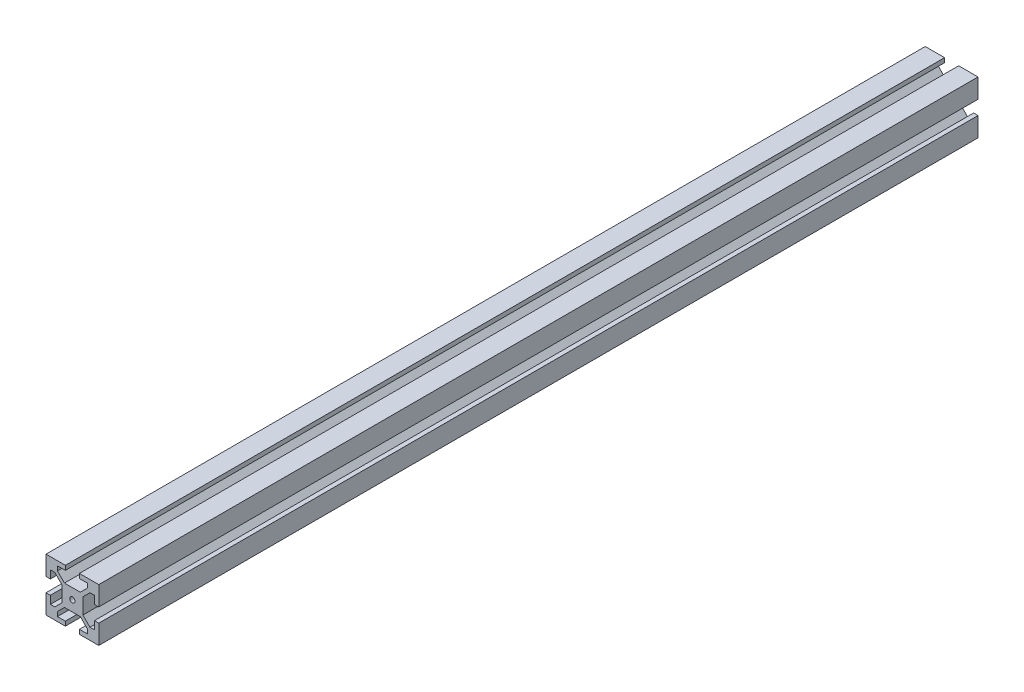
SolidWorks part; units mm, degrees
ref_plane "Front Plane" through (0, 0, 0) normal (0, 0, 1) x (1, 0, 0)
ref_plane "Top Plane" through (0, 0, 0) normal (0, 1, 0) x (1, 0, 0)
ref_plane "Right Plane" through (0, 0, 0) normal (1, 0, 0) x (0, 0, -1)
sketch "Sketch1" plane through (0, 0, 0) normal (0, 0, 1) x (1, 0, 0)
  line L1 (15, 15) -> (4, 15)
  line L2 (15, 15) -> (15, 4)
  line L3 (15, -15) -> (4, -15)
  line L4 (-15, 15) -> (-15, 4)
  line L6 (12.5, -4) -> (15, -4)
  line L7 (15, 0) -> (6, 0) construction
  line L8 (15, -4) -> (15, -15)
  line L9 (15, 4) -> (15, 0) construction
  line L10 (15, 0) -> (15, -4) construction
  line L11 (12.5, -4) -> (12.5, -8.5)
  line L12 (12.5, -8.5) -> (10, -8.5)
  line L13 (10, -8.5) -> (6, -4.5)
  line L14 (6, -4.5) -> (6, 4.5)
  line L16 (8.5, -10) -> (4.5, -6)
  line L17 (12.5, 4) -> (15, 4)
  line L18 (12.5, 4) -> (12.5, 8.5)
  line L19 (12.5, 8.5) -> (10, 8.5)
  line L20 (10, 8.5) -> (6, 4.5)
  line L21 (-15, 0) -> (15, 0) construction
  line L22 (-4.5, -6) -> (4.5, -6)
  line L23 (-8.5, -10) -> (-4.5, -6)
  line L24 (-8.5, -12.5) -> (-8.5, -10)
  line L25 (-4, -12.5) -> (-8.5, -12.5)
  line L26 (-4, -12.5) -> (-4, -15)
  line L27 (4, -12.5) -> (4, -15)
  line L28 (4, -12.5) -> (8.5, -12.5)
  line L29 (8.5, -12.5) -> (8.5, -10)
  line L30 (-10, -8.5) -> (-6, -4.5)
  line L31 (-6, 4.5) -> (-6, -4.5)
  line L32 (-10, 8.5) -> (-6, 4.5)
  line L33 (-12.5, 8.5) -> (-10, 8.5)
  line L34 (-12.5, 4) -> (-12.5, 8.5)
  line L35 (-12.5, 4) -> (-15, 4)
  line L36 (-12.5, -4) -> (-15, -4)
  line L37 (-12.5, -4) -> (-12.5, -8.5)
  line L38 (-12.5, -8.5) -> (-10, -8.5)
  line L39 (-8.5, 10) -> (-4.5, 6)
  line L40 (4.5, 6) -> (-4.5, 6)
  line L41 (8.5, 10) -> (4.5, 6)
  line L42 (8.5, 12.5) -> (8.5, 10)
  line L43 (4, 12.5) -> (8.5, 12.5)
  line L44 (4, 12.5) -> (4, 15)
  line L45 (-4, 12.5) -> (-4, 15)
  line L46 (-4, 12.5) -> (-8.5, 12.5)
  line L47 (-8.5, 12.5) -> (-8.5, 10)
  line L48 (-4, 15) -> (-15, 15)
  line L49 (4, 15) -> (-4, 15) construction
  line L50 (-15, -4) -> (-15, -15)
  line L51 (-15, 4) -> (-15, 0) construction
  line L52 (-15, 0) -> (-15, -4) construction
  line L53 (-4, -15) -> (-15, -15)
  line L54 (4, -15) -> (-4, -15) construction
  circle A0 centre (0, 0) radius 1.5
  point P6 (0, 0)
  point P21 (0, 0)
  point P54 (-6, 0)
  dimension "D7" = 3
  dimension "D6" = 8.5
  dimension "D8" = 4.5
  dimension "D2" = 30
  dimension "D1" = 8
  dimension "D3" = 2.5
  dimension "D4" = 9
  dimension "D9" = 4
extrude "Boss-Extrude1" add sketch "Sketch1" along normal blind 500
equation "\"var1\"=30"
equation "\"D2@Sketch1\"=\"var1\""
equation "\"D1@Sketch1\"=\"var1\"/3.75"
equation "\"D3@Sketch1\"=\"var1\"/12"
equation "\"D4@Sketch1\"=\"var1\"*0.3"
